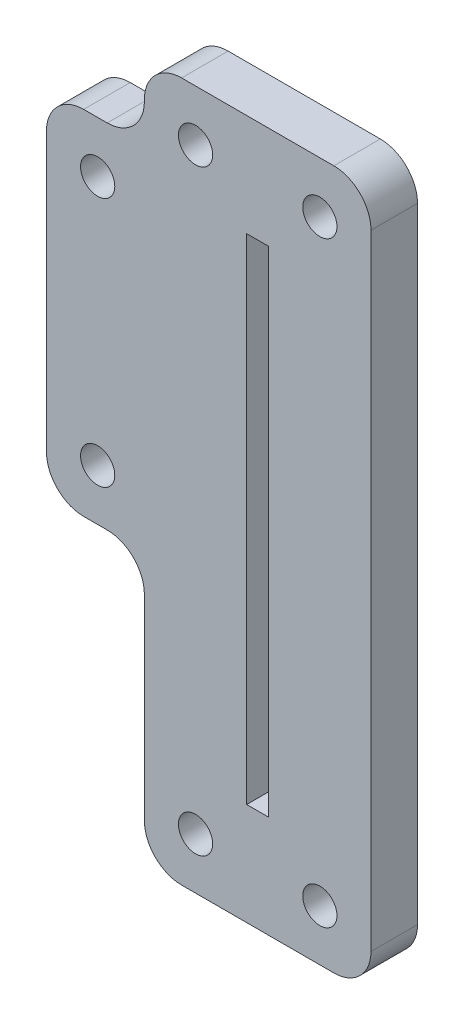
SolidWorks part; units mm, degrees
ref_plane "Front Plane" through (0, 0, 0) normal (0, 0, 1) x (1, 0, 0)
ref_plane "Top Plane" through (0, 0, 0) normal (0, 1, 0) x (1, 0, 0)
ref_plane "Right Plane" through (0, 0, 0) normal (1, 0, 0) x (0, 0, -1)
sketch "Sketch1" plane through (0, 0, 0) normal (0, 0, 1) x (1, 0, 0)
  line L0 (-31.4532, -3.5825) -> (-31.4532, -46.2225)
  line L1 (-44.3832, -1.0425) -> (-33.9932, -1.0425)
  line L2 (-53.6057, -8.7842) -> (-53.6057, -27.7707)
  line L3 (-44.3832, -48.7625) -> (-33.9932, -48.7625)
  line L5 (-39.9382, -8.0275) -> (-38.4382, -8.0275)
  line L6 (-39.9382, -8.0275) -> (-39.9382, -41.7775)
  line L7 (-39.9382, -41.7775) -> (-38.4382, -41.7775)
  line L8 (-38.4382, -8.0275) -> (-38.4382, -41.7775)
  line L9 (-51.0657, -6.2442) -> (-49.4632, -6.2442)
  line L10 (-46.9232, -3.5825) -> (-46.9232, -3.7042)
  line L11 (-46.9232, -46.2225) -> (-46.9232, -32.8507)
  line L13 (-49.4632, -30.3107) -> (-51.0657, -30.3107)
  circle A0 centre (-43.4307, -4.535) radius 1.1684
  circle A1 centre (-34.9457, -4.535) radius 1.1684
  circle A2 centre (-43.4307, -45.27) radius 1.1684
  circle A3 centre (-34.9457, -45.27) radius 1.1684
  arc A4 (-31.4532, -3.5825) -> (-33.9932, -1.0425) centre (-33.9932, -3.5825) ccw
  arc A5 (-44.3832, -1.0425) -> (-46.9232, -3.5825) centre (-44.3832, -3.5825) ccw
  arc A6 (-31.4532, -46.2225) -> (-33.9932, -48.7625) centre (-33.9932, -46.2225) cw
  arc A7 (-46.9232, -46.2225) -> (-44.3832, -48.7625) centre (-44.3832, -46.2225) ccw
  circle A8 centre (-50.1132, -9.7367) radius 1.1684
  circle A9 centre (-50.1132, -26.8182) radius 1.1684
  arc A10 (-46.9232, -32.8507) -> (-49.4632, -30.3107) centre (-49.4632, -32.8507) ccw
  arc A11 (-53.6057, -27.7707) -> (-51.0657, -30.3107) centre (-51.0657, -27.7707) ccw
  arc A12 (-46.9232, -3.7042) -> (-49.4632, -6.2442) centre (-49.4632, -3.7042) cw
  arc A13 (-53.6057, -8.7842) -> (-51.0657, -6.2442) centre (-51.0657, -8.7842) cw
  dimension "D7" = 2.3368
  dimension "D8" = 2.3368
  dimension "D9" = 2.3368
  dimension "D10" = 2.3368
  dimension "D11" = 3.4925
  dimension "D12" = 17.0815
  dimension "D13" = 3.4925
  dimension "D14" = 3.4925
  dimension "D15" = 3.4925
  dimension "D16" = 3.4925
  dimension "D17" = 3.4925
  dimension "D18" = 1.7093
  dimension "D19" = 2.54
  dimension "D23" = 2.54
  dimension "D24" = 10.175
  dimension "D21" = 10.175
  dimension "D25" = 3.4925
  dimension "D26" = 2.3368
  dimension "D27" = 2.3368
  dimension "D2" = 6.985
  dimension "D3" = 33.75
  dimension "D4" = 6.985
  dimension "D5" = 1.5
  dimension "D6" = 6.985
  dimension "D20" = 3.4925
  dimension "D22" = 3.4925
extrude "Boss-Extrude1" add sketch "Sketch1" along normal blind 3.175
